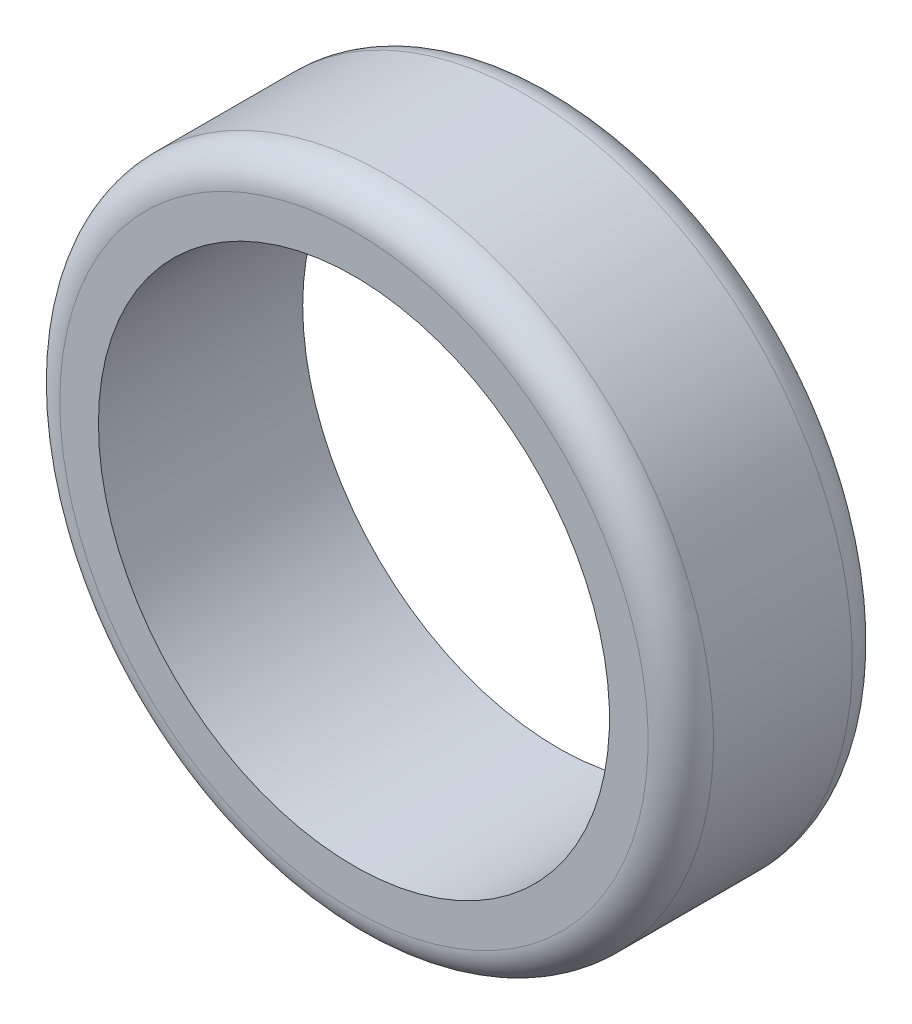
SolidWorks part; units mm, degrees
ref_plane "Front Plane" through (0, 0, 0) normal (0, 0, 1) x (1, 0, 0)
ref_plane "Top Plane" through (0, 0, 0) normal (0, 1, 0) x (1, 0, 0)
ref_plane "Right Plane" through (0, 0, 0) normal (1, 0, 0) x (0, 0, -1)
ref_plane "Plane_axle_y" through (0, -19.05, 0) normal (0, 1, 0) x (1, 0, 0)
sketch "Sk_tread_section" plane through (0, -19.05, 0) normal (0, 1, 0) x (1, 0, 0)
  line L0 (78.2002, 15.875) -> (84.201, 15.875)
  line L1 (89.281, 10.795) -> (89.281, -10.795)
  line L2 (84.201, -15.875) -> (78.2002, -15.875)
  line L3 (78.2002, -15.875) -> (78.2002, 15.875)
  line L4 (38.481, 50.8) -> (38.481, -50.8) construction
  arc A0 (84.201, 15.875) -> (89.281, 10.795) centre (84.201, 10.795) cw
  arc A1 (89.281, -10.795) -> (84.201, -15.875) centre (84.201, -10.795) cw
revolve "Rev_tread" add sketch "Sk_tread_section" angle 360 about L4
